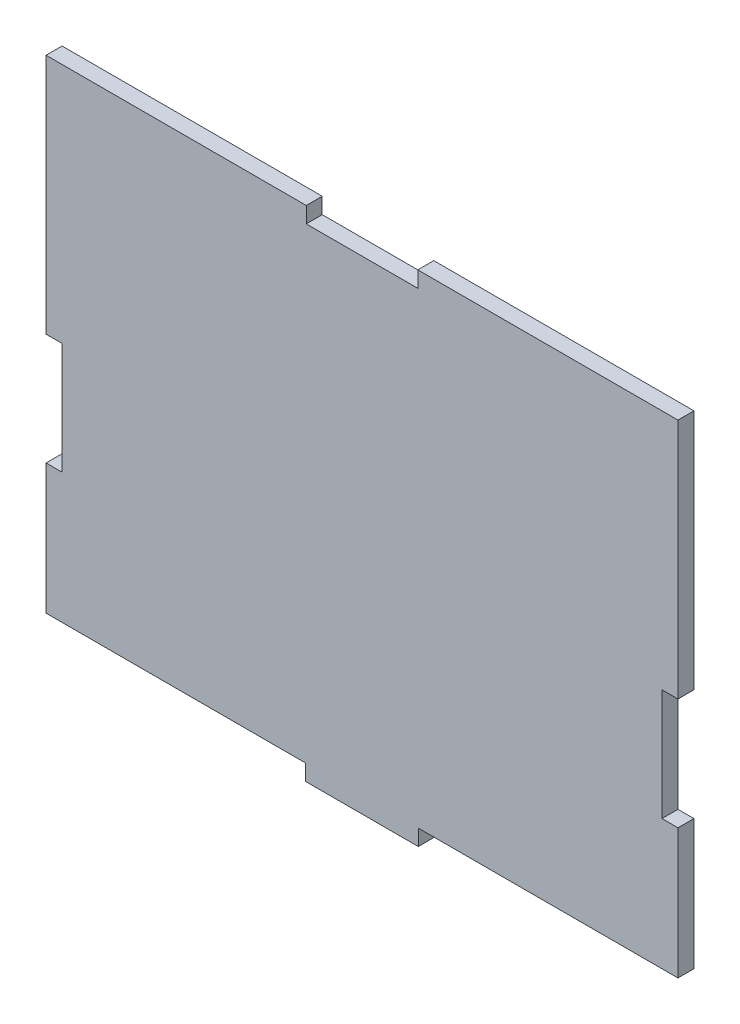
SolidWorks part; units mm, degrees
ref_plane "Front Plane" through (0, 0, 0) normal (0, 0, 1) x (1, 0, 0)
ref_plane "Top Plane" through (0, 0, 0) normal (0, 1, 0) x (1, 0, 0)
ref_plane "Right Plane" through (0, 0, 0) normal (1, 0, 0) x (0, 0, -1)
sketch "Sketch2" plane through (0, 0, 0) normal (0, 0, 1) x (1, 0, 0)
  line L0 (15, 65) -> (85, 65)
  line L1 (-85, -65) -> (-15.15, -65)
  line L2 (-85, -65) -> (-85, -30)
  line L3 (-85, 65) -> (-15, 65)
  line L4 (85, -65) -> (85, -30)
  line L5 (-85, -65) -> (85, 65) construction
  line L6 (-85, 65) -> (85, -65) construction
  line L8 (15.15, -65) -> (15.15, -69.3)
  line L9 (15.15, -69.3) -> (-15.15, -69.3)
  line L10 (-15.15, -65) -> (-15.15, -69.3)
  line L12 (15, 65) -> (15, 60.7)
  line L13 (15, 60.7) -> (-15, 60.7)
  line L14 (-15, 65) -> (-15, 60.7)
  line L15 (85, 0) -> (80.7, 0)
  line L17 (85, -30) -> (80.7, -30)
  line L18 (80.7, 0) -> (80.7, -30)
  line L19 (-85, 0) -> (-80.7, 0)
  line L21 (-85, -30) -> (-80.7, -30)
  line L22 (-80.7, 0) -> (-80.7, -30)
  line L23 (15.15, -65) -> (85, -65)
  line L24 (85, 0) -> (85, 65)
  line L25 (-85, 0) -> (-85, 65)
  point P0 (0, 0)
  point P22 (80.7, -15)
  point P23 (-80.7, -15)
  point P24 (0, -69.3)
  point P25 (0, 60.7)
  dimension "D1" = 170
  dimension "D2" = 130
  dimension "D3" = 50
  dimension "D4" = 30
  dimension "D5" = 4.3
  dimension "D6" = 30.3
  dimension "D7" = 4.3
  dimension "D8" = 4.3
  dimension "D9" = 30
extrude "Boss-Extrude1" add sketch "Sketch2" along normal blind 4.3
